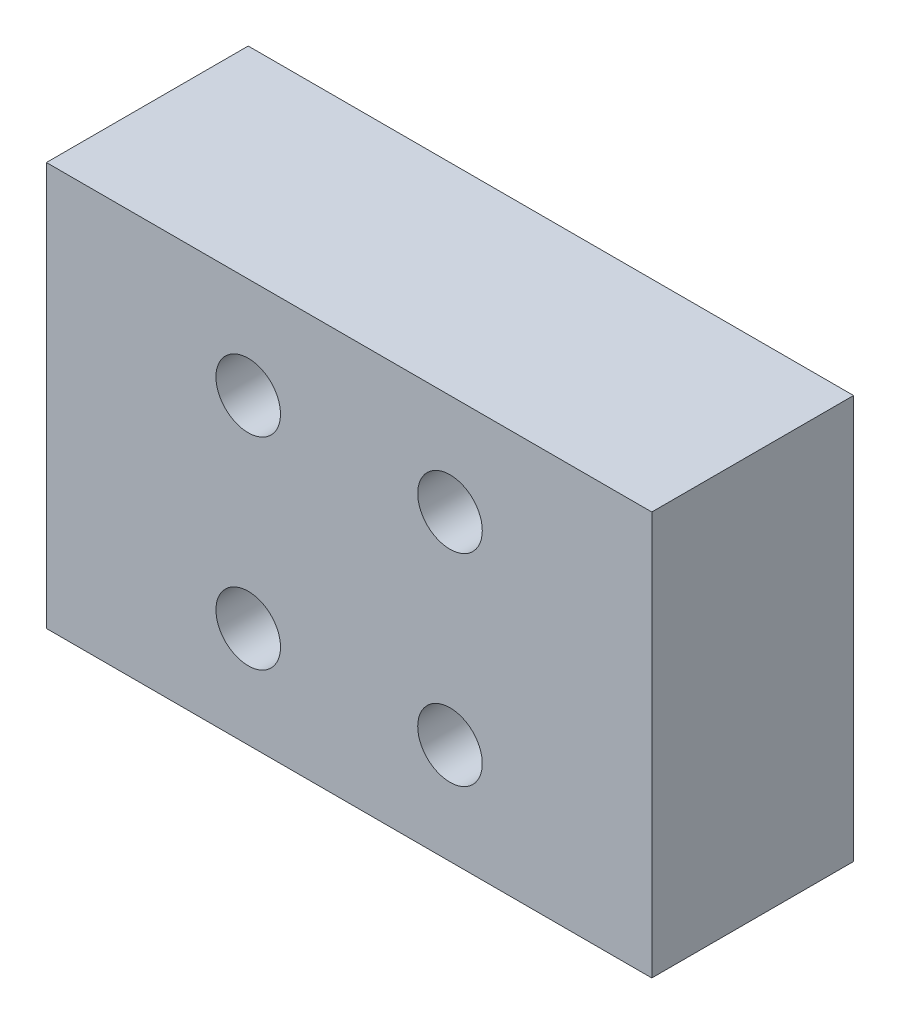
SolidWorks part; units mm, degrees
ref_plane "前视基准面" through (0, 0, 0) normal (0, 0, 1) x (1, 0, 0)
ref_plane "上视基准面" through (0, 0, 0) normal (0, 1, 0) x (1, 0, 0)
ref_plane "右视基准面" through (0, 0, 0) normal (1, 0, 0) x (0, 0, -1)
other "Configuration Table"
sketch "草图1" plane through (0, 0, 0) normal (0, 0, 1) x (1, 0, 0)
  line L1 (0, 0) -> (30, 0)
  line L2 (0, 0) -> (0, -20)
  line L3 (0, -20) -> (30, -20)
  line L4 (30, 0) -> (30, -20)
  dimension "D1" = 30
  dimension "D2" = 20
extrude "凸台-拉伸1" add sketch "草图1" along normal blind 10
sketch "草图2" plane through (0, 0, 10) normal (0, 0, 1) x (1, 0, 0)
  line L0 (15, 0) -> (15, -20) construction
  line L1 (30, 0) -> (0, 0) construction
  line L2 (0, -20) -> (30, -20) construction
  line L3 (15, -10) -> (0, -10) construction
  line L4 (0, 0) -> (0, -20) construction
  circle A1 centre (10, -5) radius 1.6
  circle A2 centre (10, -15) radius 1.6
  circle A5 centre (20, -15) radius 1.6
  circle A6 centre (20, -5) radius 1.6
  dimension "D1" = 3.2
  dimension "D2" = 5
  dimension "D3" = 5
extrude "切除-拉伸1" cut sketch "草图2" against normal through all
